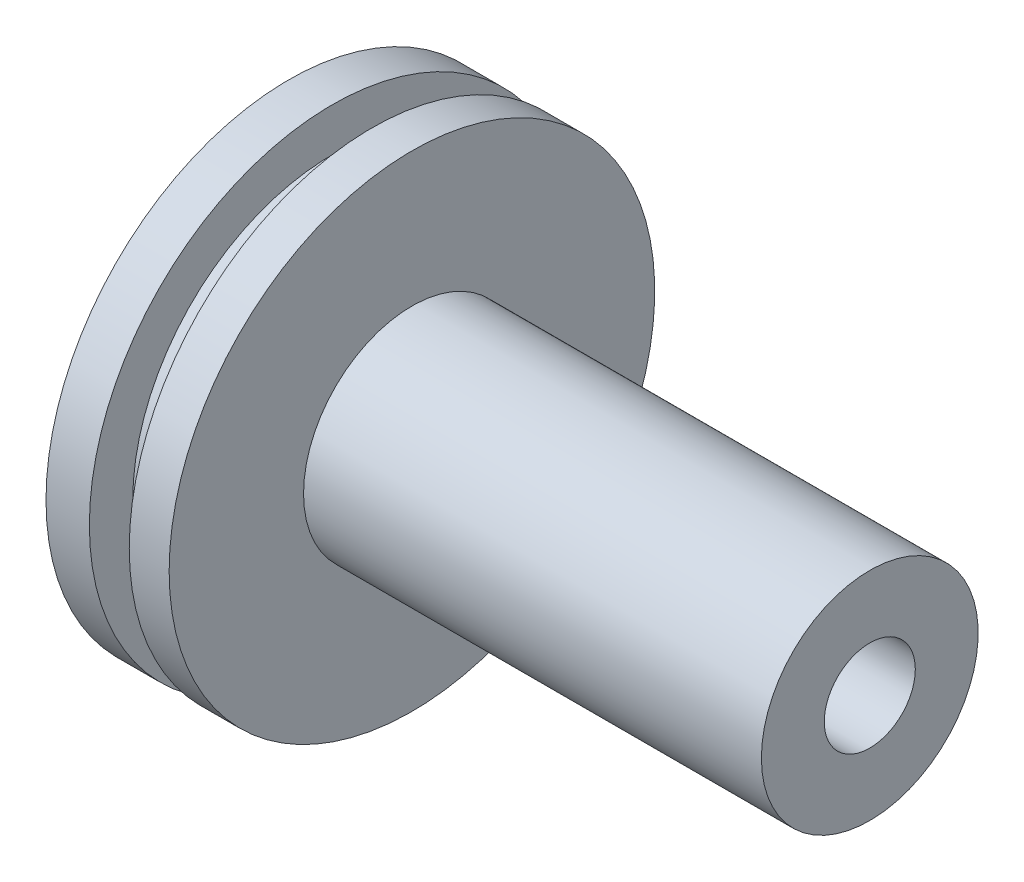
SolidWorks part; units mm, degrees
ref_plane "Спереди" through (0, 0, 0) normal (0, 0, 1) x (1, 0, 0)
ref_plane "Сверху" through (0, 0, 0) normal (0, 1, 0) x (1, 0, 0)
ref_plane "Справа" through (0, 0, 0) normal (1, 0, 0) x (0, 0, -1)
sketch "Эскиз1" plane through (0, 0, 0) normal (0, 0, 1) x (1, 0, 0)
  line L0 (0, -541.044) -> (0, 26511.1563) construction
  line L1 (-541.044, 0) -> (26511.1563, 0) construction
  line L2 (0, 0) -> (-70, 0)
  line L3 (-70, 0) -> (-70, -9)
  line L4 (-70, -9) -> (-67, -12.4511)
  line L5 (-67, -12.4511) -> (-67, -28)
  line L6 (-67, -28) -> (-62, -28)
  line L7 (-62, -28) -> (-62, -23)
  line L8 (-62, -23) -> (-57.4, -23)
  line L9 (-57.4, -23) -> (-57.4, -28)
  line L10 (-57.4, -28) -> (-52.8, -28)
  line L11 (-52.8, -28) -> (-52.8, -12.5)
  line L12 (-52.8, -12.5) -> (0, -12.5)
  line L13 (0, -12.5) -> (0, 0)
  dimension "D1" = 12.5
  dimension "D2" = 56
  dimension "D3" = 46
  dimension "D4" = 56
  dimension "D5" = 18
  dimension "D6" = 70
  dimension "D7" = 67
  dimension "D8" = 5
  dimension "D9" = 41
  dimension "D10" = 4.6
revolve "Повернуть1" add sketch "Эскиз1" angle 360 about L1
hole_wizard "Сверление под метчик M12x1.51" positions "Трехмерный эскиз3" profile "Эскиз5" hole size "M12x1.5" standard "Ansi Metric"
sketch3d "Трехмерный эскиз3"
  point P0 (0, 0, 0)
  point P4 (0, 0, 0)
sketch "Эскиз5" plane through (0, 0, 0) normal (0, 1, 0) x (0, 0, -1)
  line L0 (0, 0) -> (0, 48.1545)
  line L1 (0, 48.1545) -> (5.25, 45)
  line L2 (5.25, 45) -> (5.25, 0)
  line L5 (5.25, 0) -> (0, 0)
  line L10 (0, 48.1545) -> (-5.25, 45) construction
  line L11 (0, -6.35) -> (0, 107.95) construction
  dimension "Диаметр отверстия" = 10.5
  dimension "Глубина отверстия" = 45
  dimension "Угол заточки сверла" = 118
cosmetic thread "Условное изображение резьбы1" parameters "D2"=12
